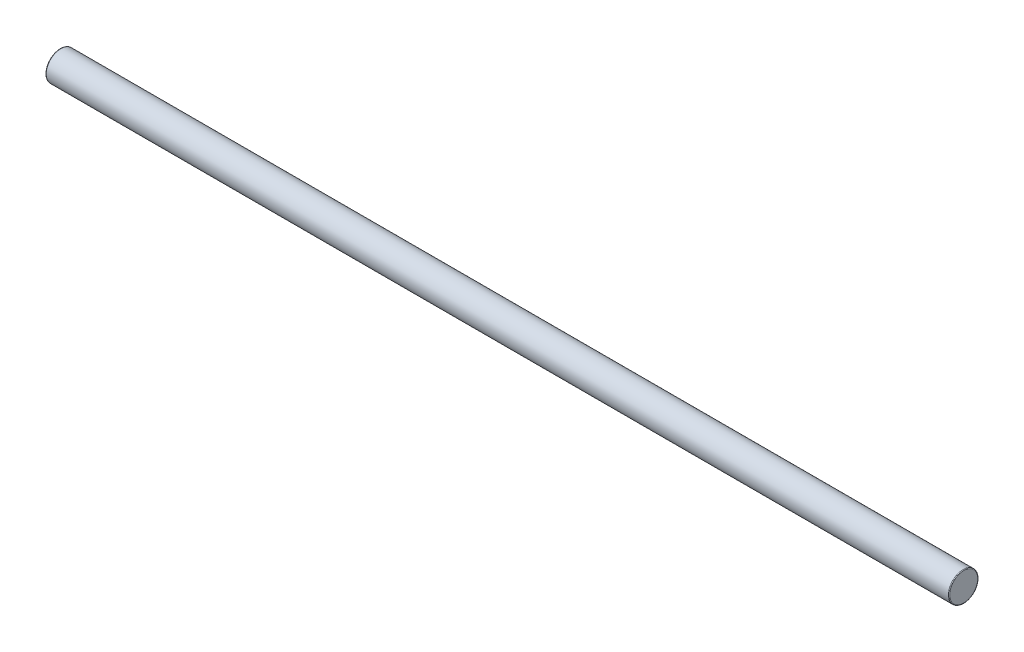
SolidWorks part; units mm, degrees
ref_plane "Front Plane" through (0, 0, 0) normal (1, 0, 0) x (0, 1, 0)
ref_plane "Top Plane" through (0, 0, 0) normal (0, 0, 1) x (0, 1, 0)
ref_plane "Right Plane" through (0, 0, 0) normal (0, 1, 0) x (-1, 0, 0)
sketch "Sketch1" plane through (0, 0, 0) normal (1, 0, 0) x (0, 1, 0)
  circle A0 centre (0, 0) radius 31.7309
extrude "Boss-Extrude1" add sketch "Sketch1" along normal blind 1952.752
fillet "Fillet1" radius 1.524 2 edges at (1952.752, 0, -31.7309) (0, 0, -31.7309)
